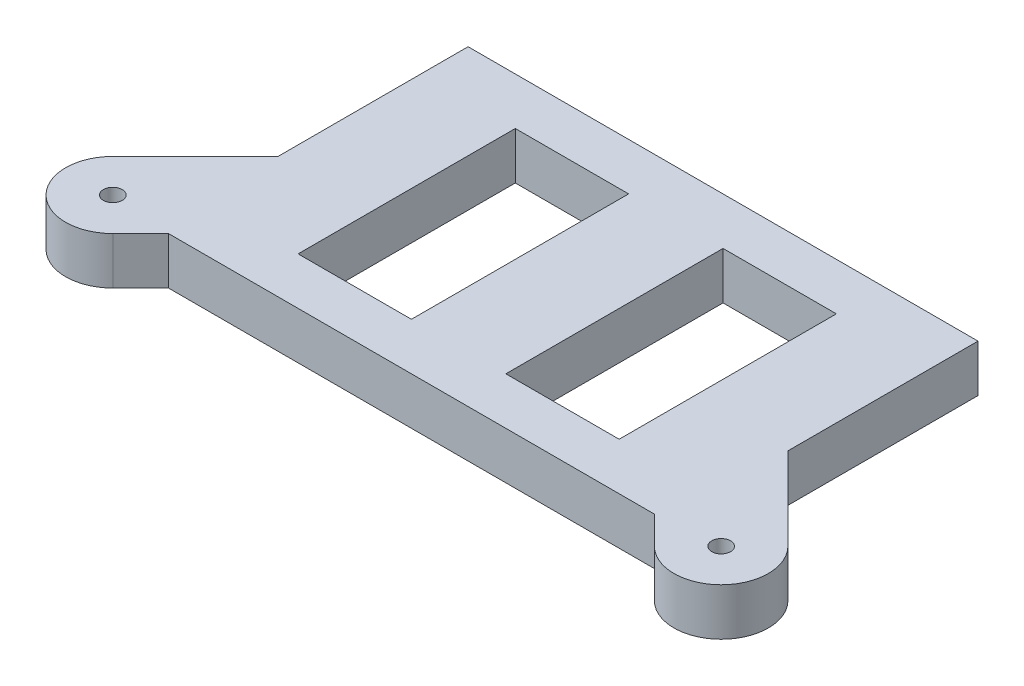
SolidWorks part; units mm, degrees
ref_plane "Front Plane" through (0, 0, 0) normal (0, 0, 1) x (1, 0, 0)
ref_plane "Top Plane" through (0, 0, 0) normal (0, 1, 0) x (1, 0, 0)
ref_plane "Right Plane" through (0, 0, 0) normal (1, 0, 0) x (0, 0, -1)
sketch "Sketch1" plane through (0, 0, 0) normal (0, 1, 0) x (1, 0, 0)
  line L1 (0, 0) -> (54, 0)
  line L2 (0, 0) -> (0, 33)
  line L3 (0, 33) -> (54, 33)
  line L4 (54, 0) -> (54, 33)
  line L5 (10, 28) -> (22, 28)
  line L6 (10, 28) -> (10, 5)
  line L7 (10, 5) -> (22, 5)
  line L8 (22, 28) -> (22, 5)
  line L9 (32, 28) -> (44, 28)
  line L10 (32, 28) -> (32, 5)
  line L11 (32, 5) -> (44, 5)
  line L12 (44, 28) -> (44, 5)
  dimension "D1" = 12
  dimension "D2" = 23
  dimension "D3" = 10
  dimension "D4" = 5
  dimension "D5" = 5
  dimension "D6" = 10
  dimension "D7" = 12
  dimension "D8" = 23
  dimension "D9" = 10
  dimension "D10" = 5
extrude "Boss-Extrude1" add sketch "Sketch1" along normal blind 5
sketch "Sketch2" plane through (0, 0, 0) normal (0, 1, 0) x (1, 0, 0)
  line L0 (62.1518, 21.8) -> (-9.5147, 21.8)
  line L1 (54, 33) -> (0, 33) construction
  line L3 (38, 29.3512) -> (38, 10.3952)
  line L4 (16, 29.3512) -> (16, 10.3952)
  line L5 (54, 0) -> (54, 33) construction
  line L6 (0, 33) -> (0, 0) construction
  line L7 (38, 21.8) -> (59.2132, 0.5868)
  line L8 (16, 21.8) -> (-5.2132, 0.5868)
  dimension "D1" = 11.2
  dimension "D2" = 16
  dimension "D3" = 16
  dimension "D4" = 30
  dimension "D5" = 30
  dimension "D6" = 45
  dimension "D7" = 45
sketch "Sketch4" plane through (0, 0, 0) normal (0, -1, 0) x (1, 0, 0)
  line L0 (62.7487, -4.1223) -> (54, -12.8711)
  line L1 (54, 0) -> (54, -33) construction
  line L2 (55.6777, 2.9487) -> (52.7289, 0)
  line L3 (0, 0) -> (54, 0) construction
  line L4 (54, -12.8711) -> (54, 0)
  line L5 (54, 0) -> (52.7289, 0)
  line L6 (-8.7487, -4.1223) -> (0, -12.8711)
  line L7 (0, -33) -> (0, 0) construction
  line L8 (-1.6777, 2.9487) -> (1.2711, 0)
  line L9 (0, -12.8711) -> (0, 0)
  line L10 (0, 0) -> (1.2711, 0)
  circle A0 centre (59.2132, -0.5868) radius 1
  circle A1 centre (-5.2132, -0.5868) radius 1
  arc A2 (62.7487, -4.1223) -> (55.6777, 2.9487) centre (59.2132, -0.5868) ccw
  arc A3 (-1.6777, 2.9487) -> (-8.7487, -4.1223) centre (-5.2132, -0.5868) ccw
  dimension "D1" = 2
  dimension "D2" = 2
  dimension "D3" = 10
  dimension "D4" = 10
  dimension "D5" = 135
  dimension "D6" = 135
extrude "Boss-Extrude2" add sketch "Sketch4" against normal blind 5
